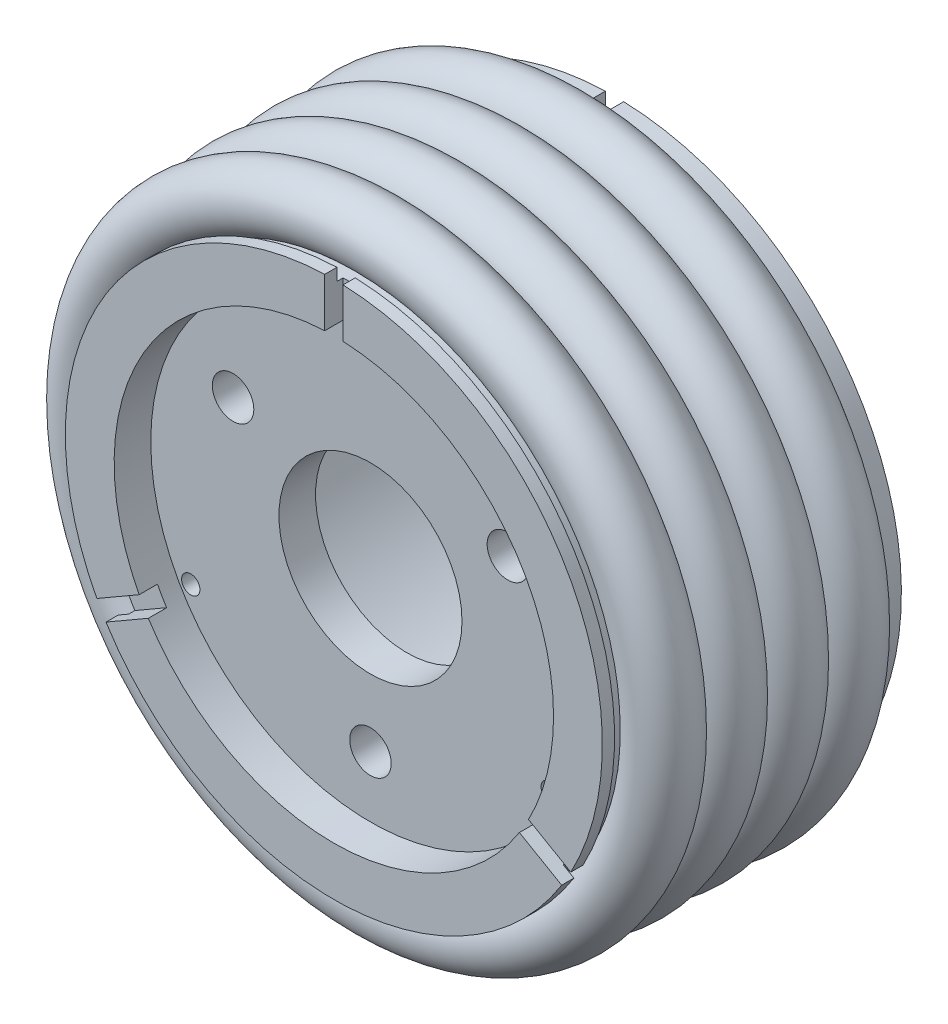
SolidWorks part; units mm, degrees
material "1060 合金"
ref_plane "前视基准面" through (0, 0, 0) normal (0, 0, 1) x (1, 0, 0)
ref_plane "上视基准面" through (0, 0, 0) normal (0, 1, 0) x (1, 0, 0)
ref_plane "右视基准面" through (0, 0, 0) normal (1, 0, 0) x (0, 0, -1)
sketch "草图1" plane through (0, 0, 0) normal (1, 0, 0) x (0, 0, -1)
  line L0 (-11.5, 0) -> (-11.5, 48.2279) construction
  line L1 (-11.5, 0) -> (75.147, 0) construction
  line L2 (0, 21) -> (0, -6.6133) construction
  line L3 (-11.5, 21) -> (-11.5, 18)
  line L4 (-8.5, 7.5) -> (-8.5, 18)
  line L5 (-11.5, 21) -> (11.5, 21)
  line L6 (11.5, 18) -> (11.5, 21)
  line L7 (-11.5, 18) -> (-8.5, 18)
  line L9 (11.5, 18) -> (-5.5, 18)
  line L10 (-5.5, 7.5) -> (-5.5, 18)
  line L13 (-5.5, 7.5) -> (-8.5, 7.5)
  dimension "D1" = 7.5
  dimension "D2" = 3
  dimension "D3" = 18
  dimension "D4" = 3
  dimension "D5" = 23
  dimension "D6" = 3
revolve "旋转1" add sketch "草图1" angle 360 about L1
hole_wizard "M3 间隙孔1" positions "草图3" profile "草图2" hole size "M3" standard "GB"
sketch "草图3" plane through (0, 0, 8.5) normal (0, 0, 1) x (1, 0, 0)
  line L0 (0, 0) -> (24.1812, 13.961) construction
  line L1 (0, 0) -> (0, 29.0656) construction
  circle A0 centre (0, 0) radius 13 construction
  point P0 (11.2583, 6.5)
  point P24 (0, -13)
  point P25 (-11.2583, 6.5)
  point P26 (11.2583, 6.5) [skipped]
  dimension "D1" = 26
  dimension "D3" = 60
  dimension "D2" = 3
sketch "草图2" plane through (11.2583, 6.5, 8.5) normal (1, 0, 0) x (0, -1, 0)
  line L0 (0, 0) -> (0, 24.0215)
  line L1 (0, 24.0215) -> (1.7, 23)
  line L2 (1.7, 23) -> (1.7, 0)
  line L5 (1.7, 0) -> (0, 0)
  line L10 (0, 24.0215) -> (-1.7, 23) construction
  line L11 (0, -6.35) -> (0, 107.95) construction
  dimension "孔直径" = 3.4
  dimension "孔深度" = 23
  dimension "导头角度" = 118
sketch "草图4" plane through (0, 0, 0) normal (0, 1, 0) x (1, 0, 0)
  line L0 (0, -10.5473) -> (0, 33.1049) construction
  line L2 (21, -11.5) -> (22, -11.5)
  line L3 (21, -11.5) -> (21, -10.5)
  line L4 (21, -10.5) -> (22, -10.5)
  line L5 (22, -11.5) -> (22, -10.5)
  line L6 (21, 11.5) -> (23.5, 11.5)
  line L7 (21, 11.5) -> (21, 9.5)
  line L8 (21, 9.5) -> (23.5, 9.5)
  line L9 (23.5, 11.5) -> (23.5, 9.5)
  dimension "D1" = 2
  dimension "D2" = 2.5
  dimension "D3" = 1
  dimension "D4" = 1
revolve "台阶" add sketch "草图4" angle 360 about L0
sketch "草图6" plane through (0, 0, 0) normal (0, 1, 0) x (1, 0, 0)
  line L2 (22, -10.5) -> (-22, -10.5) construction
  line L3 (22, -10.5) -> (-22, -10.5) construction
  line L4 (-23.5, 9.5) -> (23.5, 9.5) construction
  line L5 (-23.5, 9.5) -> (23.5, 9.5) construction
  line L7 (0, 14.3969) -> (0, -17.7582) construction
  line L8 (23.5, 11.5) -> (-23.5, 11.5) construction
  line L9 (-0.75, 9.5) -> (0.75, 9.5)
  line L10 (-0.75, 9.5) -> (-0.75, 11.5)
  line L11 (-0.75, 11.5) -> (0.75, 11.5)
  line L12 (0.75, 9.5) -> (0.75, 11.5)
  line L13 (-0.75, 9.5) -> (0.75, 11.5) construction
  line L14 (-0.75, 11.5) -> (0.75, 9.5) construction
  line L15 (-22, -11.5) -> (22, -11.5) construction
  line L16 (-0.75, -10) -> (0.75, -10)
  line L17 (-0.75, -10) -> (-0.75, -11.5)
  line L18 (-0.75, -11.5) -> (0.75, -11.5)
  line L19 (0.75, -10) -> (0.75, -11.5)
  line L20 (-0.75, -10) -> (0.75, -11.5) construction
  line L21 (-0.75, -11.5) -> (0.75, -10) construction
  point P2 (0, 10.5)
  point P13 (0, -10.75)
  dimension "D1" = 1.5
  dimension "D2" = 1.5
  dimension "D3" = 1.5
extrude "切除-拉伸1" cut sketch "草图6" along normal through all
sketch "草图7" plane through (0, 0, 8.5) normal (0, 0, 1) x (1, 0, 0)
  line L0 (0, 27.5413) -> (0, -29.9529) construction
  line L1 (-34.8705, 0) -> (0, 0) construction
  circle A0 centre (0, 17) radius 0.75
  circle A1 centre (0, 0) radius 18 construction
  circle A2 centre (0, 0) radius 18 construction
  point P11 (0, 18)
  dimension "D1" = 1.5
  dimension "D2" = 1
extrude "切除-拉伸2" cut sketch "草图7" against normal through all
pattern_circular "阵列(圆周)1" count 3 over 360 about axis through (0, 0, 0) along (0, 0, 1) of "切除-拉伸1", "切除-拉伸2"
sketch "草图5" plane through (0, 0, 0) normal (0, 1, 0) x (1, 0, 0)
  line L0 (21, -10.5) -> (21, 9.5) construction
  line L1 (-23.5, 9.5) -> (23.5, 9.5) construction
  line L2 (0, 0) -> (0, 30.1002) construction
  circle A0 centre (23.5, 7) radius 2.5
  dimension "D1" = 5
revolve "旋转3" add sketch "草图5" angle 360 about L2
pattern_linear "阵列(线性)2" count 4 spacing 5 along (0, 0, 1) of bodies 105
